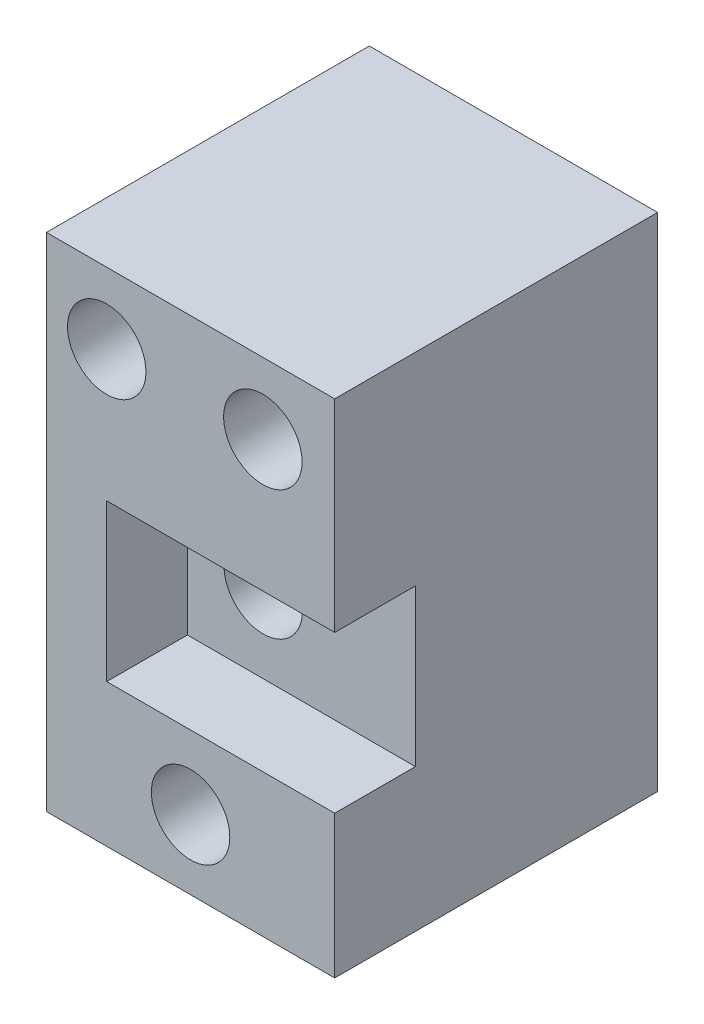
SolidWorks part; units mm, degrees
ref_plane "Plan de face" through (0, 0, 0) normal (0, 0, 1) x (1, 0, 0)
ref_plane "Plan de dessus" through (0, 0, 0) normal (0, 1, 0) x (1, 0, 0)
ref_plane "Plan de droite" through (0, 0, 0) normal (1, 0, 0) x (0, 0, -1)
sketch "Esquisse1" plane through (0, 0, 0) normal (0, 0, 1) x (1, 0, 0)
  line L1 (-6.25, -10.875) -> (6.25, -10.875)
  line L2 (-6.25, -10.875) -> (-6.25, 10.875)
  line L3 (-6.25, 10.875) -> (6.25, 10.875)
  line L4 (6.25, -10.875) -> (6.25, 10.875)
  line L5 (-6.25, -10.875) -> (6.25, 10.875) construction
  line L6 (-6.25, 10.875) -> (6.25, -10.875) construction
  point P0 (0, 0)
  dimension "D1" = 21.75
  dimension "D2" = 12.5
extrude "Boss.-Extru.3" add sketch "Esquisse1" along normal blind 14
sketch "Esquisse9" plane through (0, 0, 14) normal (0, 0, 1) x (1, 0, 0)
  line L0 (-3.6356, -4.6863) -> (-3.6356, 2.1017)
  line L1 (-3.6356, -4.6863) -> (6.9438, -4.6863)
  line L2 (-3.6356, 2.1017) -> (6.9438, 2.1017)
  line L3 (6.9438, -4.6863) -> (6.9438, 2.1017)
extrude "Enlèv. mat.-Extru.7" cut sketch "Esquisse9" against normal blind 3.5
hole_wizard "Dégagement M32" positions "Esquisse17" profile "Esquisse16" hole size "M3" standard "JIS" end condition through all
sketch "Esquisse17" plane through (0, 0, 14) normal (0, 0, 1) x (1, 0, 0)
  point P0 (-0.35, -1.3062)
sketch "Esquisse16" plane through (-0.35, -1.3062, 14) normal (1, 0, 0) x (0, -1, 0)
  line L0 (0, 0) -> (0, 14)
  line L1 (0, 14) -> (1.7, 14)
  line L2 (1.7, 14) -> (1.7, 0)
  line L5 (1.7, 0) -> (0, 0)
  line L11 (0, -6.35) -> (0, 107.95) construction
  dimension "Diamètre du perçage jusqu'au prochain" = 3.4
  dimension "Profondeur du perçage jusqu'au prochain" = 14
hole_wizard "Dégagement M33" positions "Esquisse20" profile "Esquisse18" hole size "M3" standard "JIS" end condition through all
sketch "Esquisse20" plane through (0, 0, 14) normal (0, 0, 1) x (1, 0, 0)
  point P0 (-3.6356, 7.7949)
  point P2 (3.1342, 7.7949)
  point P4 (0, -7.8658)
sketch "Esquisse18" plane through (-3.6356, 7.7949, 14) normal (1, 0, 0) x (0, -1, 0)
  line L0 (0, 0) -> (0, 14)
  line L1 (0, 14) -> (1.7, 14)
  line L2 (1.7, 14) -> (1.7, 0)
  line L5 (1.7, 0) -> (0, 0)
  line L11 (0, -6.35) -> (0, 107.95) construction
  dimension "Diamètre du perçage jusqu'au prochain" = 3.4
  dimension "Profondeur du perçage jusqu'au prochain" = 14
